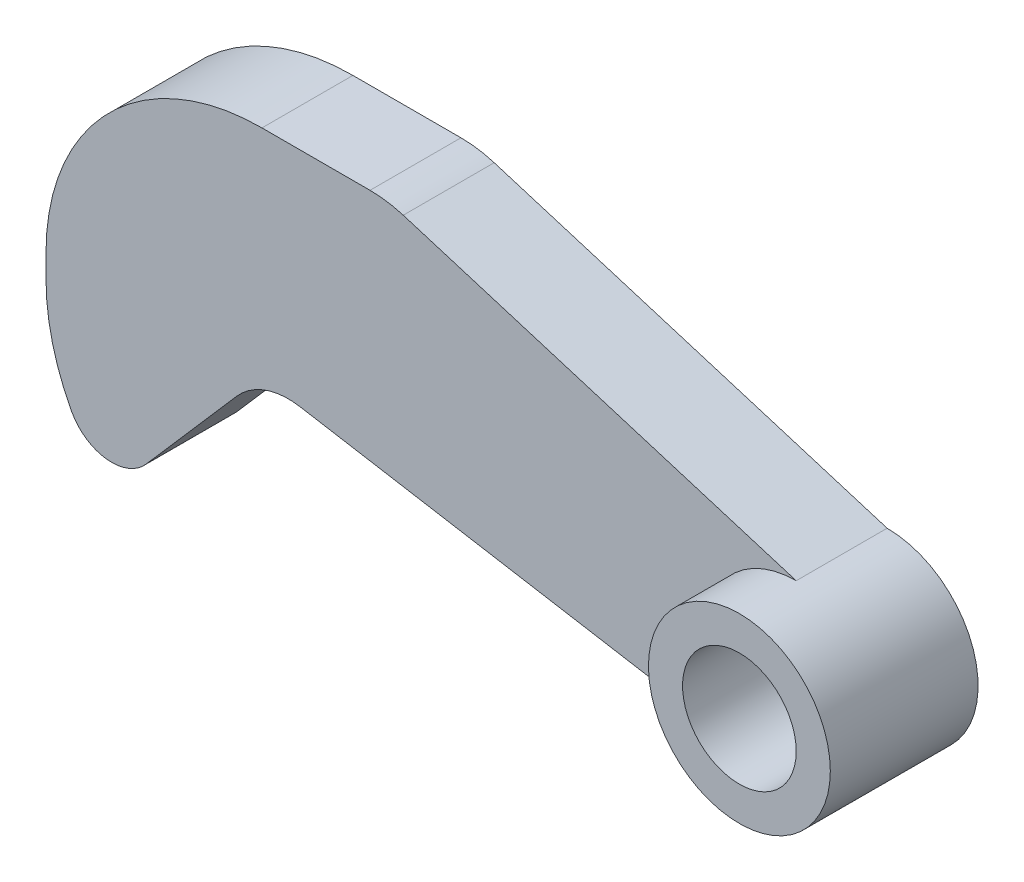
SolidWorks part; units mm, degrees
ref_plane "Plano frontal" through (0, 0, 0) normal (0, 0, 1) x (1, 0, 0)
ref_plane "Plano superior" through (0, 0, 0) normal (0, 1, 0) x (1, 0, 0)
ref_plane "Plano direito" through (0, 0, 0) normal (1, 0, 0) x (0, 0, -1)
sketch "Esboço1" plane through (0, 0, 0) normal (0, 0, 1) x (1, 0, 0)
  line L0 (7, 10) -> (7, -0.4362) construction
  line L1 (3.1604, 0.2174) -> (23.6766, -3.2747)
  line L2 (-8, -0.5) -> (-8, 0.5)
  line L3 (1.5, 10) -> (6.2532, 10)
  line L4 (7, 0.5) -> (25, 0.5) construction
  line L5 (25, 4.5) -> (7.7142, 9.7818)
  line L7 (-3.6001, -5.3593) -> (0.3942, -0.7704)
  circle A0 centre (25, 0.5) radius 4
  arc A1 (-8, 0.5) -> (1.5, 10) centre (1.5, 0.5) cw
  arc A2 (-6.871, -4.9919) -> (-8, -0.5) centre (1.5, -0.5) cw
  arc A3 (0.3942, -0.7704) -> (3.1604, 0.2174) centre (2.657, -2.7401) cw
  arc A4 (6.2532, 10) -> (7.7142, 9.7818) centre (6.2532, 5) cw
  arc A5 (-3.6001, -5.3593) -> (-6.871, -4.9919) centre (-5.1087, -4.0462) cw
  point P8 (-8, 10)
  dimension "D3" = 9.5
  dimension "D4" = 18
  dimension "D2" = 9.5
  dimension "D5" = 3
  dimension "D6" = 8
  dimension "D7" = 2
  dimension "D1" = 15
extrude "Ressalto-extrusão1" add sketch "Esboço1" along normal blind 4
sketch "Esboço3" plane through (0, 0, 4) normal (0, 0, 1) x (1, 0, 0)
  circle A0 centre (25, 0.5) radius 4
  dimension "D1" = 8
extrude "Ressalto-extrusão2" add sketch "Esboço3" along normal blind 2.5
sketch "Esboço5" plane through (0, 0, 6.5) normal (0, 0, 1) x (1, 0, 0)
  circle A0 centre (25, 0.5) radius 2.5
  dimension "D1" = 5
extrude "Corte-extrusão1" cut sketch "Esboço5" against normal blind 5.5
